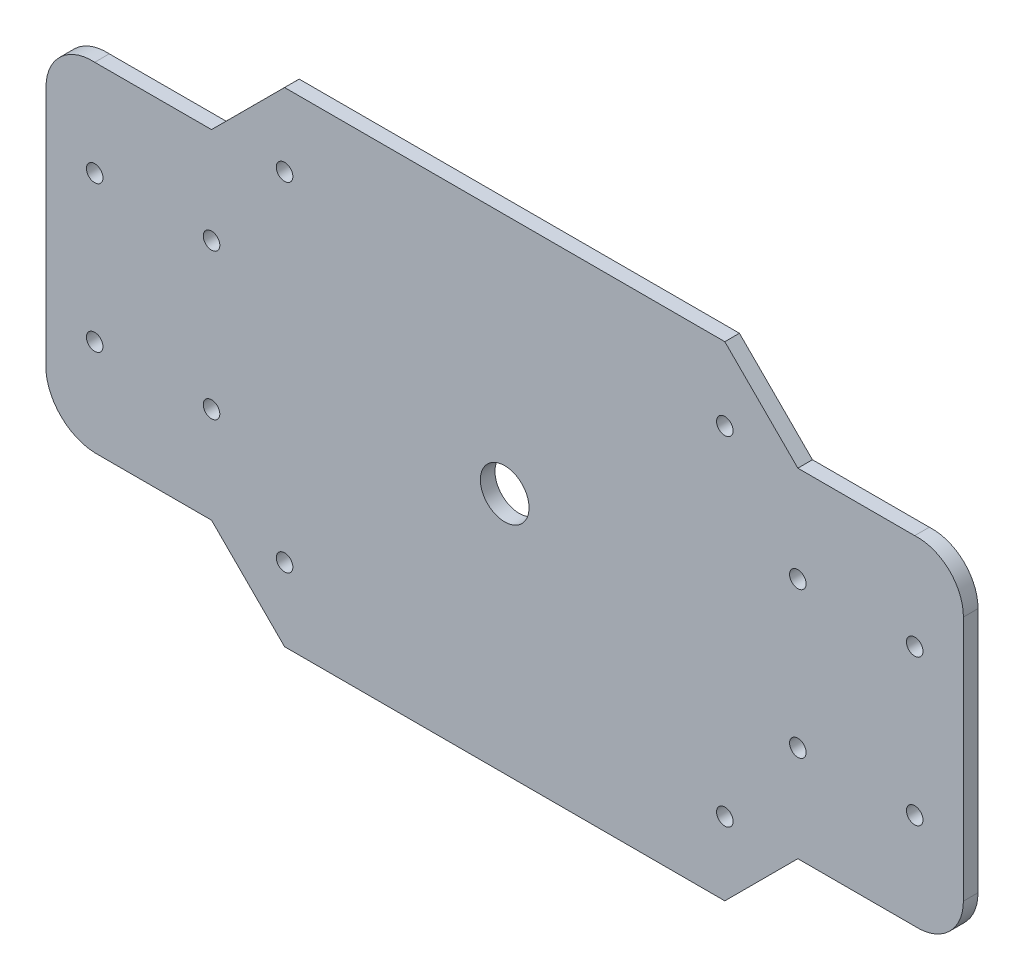
SolidWorks part; units mm, degrees
ref_plane "Front Plane" through (0, 0, 0) normal (0, 0, 1) x (1, 0, 0)
ref_plane "Top Plane" through (0, 0, 0) normal (0, 1, 0) x (1, 0, 0)
ref_plane "Right Plane" through (0, 0, 0) normal (1, 0, 0) x (0, 0, -1)
sketch "Sketch2" plane through (0, 0, 0) normal (0, 0, 1) x (1, 0, 0)
  line L0 (-49.4111, -41.7129) -> (-34.4111, -26.7241)
  line L5 (-73.4111, -41.7353) -> (-49.4111, -41.7129)
  line L7 (-73.4111, -111.1931) -> (-49.4111, -111.1931)
  line L9 (-34.4111, -26.7241) -> (56.0129, -26.7241)
  line L10 (56.0129, -26.7241) -> (71.0129, -41.7241)
  line L11 (-49.4111, -111.1931) -> (-34.4111, -126.1931)
  line L12 (-34.4111, -126.1931) -> (56.0129, -126.1931)
  line L13 (56.0129, -126.1931) -> (71.0129, -111.1931)
  line L14 (71.0129, -41.7241) -> (95.0129, -41.7241)
  line L15 (71.0129, -111.1931) -> (95.0129, -111.1931)
  line L18 (-83.4111, -51.1621) -> (-83.4111, -101.7478)
  line L19 (105.0138, -51.2106) -> (105.0093, -101.7537)
  arc A0 (-73.4111, -41.7353) -> (-83.4111, -51.1621) centre (-73.9609, -51.1694) ccw
  arc A1 (-83.4111, -101.7478) -> (-73.4111, -111.1931) centre (-72.9534, -100.6922) ccw
  arc A2 (105.0138, -51.2106) -> (95.0129, -41.7241) centre (95.5638, -51.1582) ccw
  arc A3 (95.0129, -111.1931) -> (105.0093, -101.7537) centre (95.5591, -101.7587) ccw
  circle A4 centre (-49.4111, -61.4586) radius 1.7
  circle A5 centre (-73.4111, -61.4586) radius 1.7
  circle A6 centre (-73.4111, -91.4586) radius 1.7
  circle A7 centre (-49.4111, -91.4586) radius 1.7
  circle A8 centre (95.0129, -91.4586) radius 1.7
  circle A9 centre (71.0129, -91.4586) radius 1.7
  circle A10 centre (95.0129, -61.4586) radius 1.7
  circle A11 centre (71.0129, -61.4586) radius 1.7
  circle A12 centre (10.8009, -76.383) radius 5
  circle A13 centre (-34.4111, -41.7241) radius 1.7
  circle A14 centre (-34.4111, -111.1931) radius 1.7
  circle A15 centre (56.0129, -111.1931) radius 1.7
  circle A16 centre (56.0129, -41.7241) radius 1.7
  point P46 (83.0129, -41.7241)
  point P47 (-61.4111, -111.1931)
  point P48 (10.8009, -126.1931)
  point P51 (-61.4111, -41.7241)
  point P52 (10.8009, -26.7241)
  dimension "D1" = 24
  dimension "D8" = 30
  dimension "D12" = 90.424
  dimension "D15" = 15
  dimension "D16" = 15
  dimension "D22" = 19.7345
  dimension "D2" = 30
  dimension "D3" = 90.424
  dimension "D4" = 24
  dimension "D5" = 30
  dimension "D6" = 24
  dimension "D7" = 24
  dimension "D9" = 30
  dimension "D10" = 69.469
  dimension "D11" = 69.469
  dimension "D13" = 15
  dimension "D14" = 15
  dimension "D17" = 15
  dimension "D18" = 15
  dimension "D19" = 19.7345
  dimension "D20" = 15
  dimension "D21" = 15
  dimension "D23" = 15
  dimension "D24" = 15
  dimension "D25" = 10
  dimension "D26" = 10
extrude "Boss-Extrude4" add sketch "Sketch2" along normal blind 3
